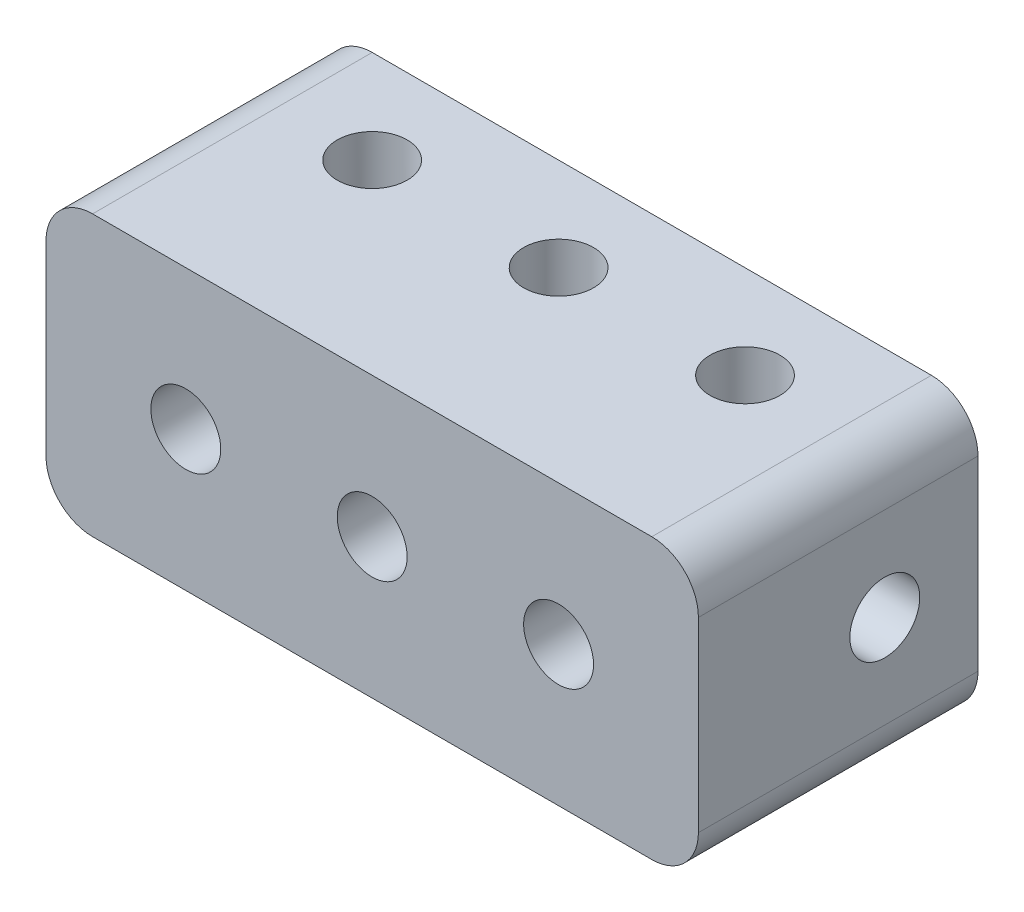
SolidWorks part; units mm, degrees
ref_plane "Front Plane" through (0, 0, 0) normal (0, 0, 1) x (1, 0, 0)
ref_plane "Top Plane" through (0, 0, 0) normal (0, 1, 0) x (1, 0, 0)
ref_plane "Right Plane" through (0, 0, 0) normal (1, 0, 0) x (0, 0, -1)
sketch "Sketch2" plane through (0, 0, 0) normal (0, 0, 1) x (1, 0, 0)
  line L1 (3.175, 0) -> (41.275, 0)
  line L2 (0, 3.175) -> (0, 15.875)
  line L3 (3.175, 19.05) -> (41.275, 19.05)
  line L4 (44.45, 3.175) -> (44.45, 15.875)
  arc A0 (0, 15.875) -> (3.175, 19.05) centre (3.175, 15.875) cw
  arc A1 (41.275, 19.05) -> (44.45, 15.875) centre (41.275, 15.875) cw
  arc A2 (3.175, 0) -> (0, 3.175) centre (3.175, 3.175) cw
  arc A3 (41.275, 0) -> (44.45, 3.175) centre (41.275, 3.175) ccw
  point P7 (0, 19.05)
  point P10 (44.45, 19.05)
  point P13 (0, 0)
  point P16 (44.45, 0)
  dimension "D3" = 3.175
  dimension "D4" = 3.175
  dimension "D5" = 3.175
  dimension "D6" = 3.175
  dimension "D1" = 44.45
  dimension "D2" = 19.05
extrude "Boss-Extrude1" add sketch "Sketch2" along normal blind 19.05
sketch "Sketch3" plane through (0, 0, 0) normal (0, 0, -1) x (-1, 0, 0)
  line L0 (-34.925, 9.525) -> (-9.525, 9.525) construction
  line L1 (-34.925, 14.2875) -> (-9.525, 14.2875)
  line L2 (-34.925, 4.7625) -> (-9.525, 4.7625)
  line L3 (-41.275, 19.05) -> (-3.175, 19.05) construction
  line L4 (-3.175, 0) -> (-41.275, 0) construction
  line L6 (0, 15.875) -> (0, 3.175) construction
  line L7 (-44.45, 3.175) -> (-44.45, 15.875) construction
  arc A0 (-34.925, 14.2875) -> (-34.925, 4.7625) centre (-34.925, 9.525) ccw
  arc A1 (-9.525, 4.7625) -> (-9.525, 14.2875) centre (-9.525, 9.525) ccw
  point P2 (-22.225, 9.525)
  point P15 (0, 0)
  dimension "D3" = 9.525
  dimension "D4" = 9.525
  dimension "D1" = 4.7625
  dimension "D2" = 4.7625
extrude "Cut-Extrude1" cut sketch "Sketch3" against normal blind 14.1224
sketch "Sketch4" plane through (0, 19.05, 0) normal (0, 1, 0) x (1, 0, 0)
  line L0 (44.45, -19.05) -> (44.45, 0) construction
  line L1 (41.275, -19.05) -> (3.175, -19.05) construction
  line L2 (0, -19.05) -> (0, 0) construction
  circle A0 centre (34.925, -6.35) radius 2.3812
  circle A1 centre (22.225, -6.35) radius 2.3813
  circle A2 centre (9.525, -6.35) radius 2.3812
  point P8 (23.4271, -6.8938)
  point P11 (7.6432, -7.3373)
  dimension "D1" = 9.525
  dimension "D2" = 12.7
  dimension "D3" = 4.7625
  dimension "D4" = 4.7625
  dimension "D5" = 4.7625
  dimension "D6" = 9.525
  dimension "D7" = 12.7
  dimension "D8" = 12.7
  dimension "D9" = 12.7
extrude "Cut-Extrude2" cut sketch "Sketch4" against normal through all both and the other way through all
sketch "Sketch5" plane through (44.45, 0, 0) normal (1, 0, 0) x (0, 0, -1)
  line L0 (0, 3.175) -> (0, 15.875) construction
  line L1 (-19.05, 0) -> (0, 0) construction
  circle A0 centre (-6.35, 9.525) radius 2.3813
  dimension "D1" = 6.35
  dimension "D2" = 4.7625
  dimension "D3" = 9.525
extrude "Cut-Extrude3" cut sketch "Sketch5" against normal through all both and the other way through all
sketch "Sketch7" plane through (0, 0, 19.05) normal (0, 0, 1) x (1, 0, 0)
  line L0 (44.45, 3.175) -> (44.45, 15.875) construction
  line L1 (0, 15.875) -> (0, 3.175) construction
  line L2 (3.175, 0) -> (41.275, 0) construction
  circle A0 centre (22.225, 9.525) radius 2.3813
  circle A1 centre (34.925, 9.525) radius 2.3812
  circle A2 centre (9.525, 9.525) radius 2.3813
  dimension "D1" = 4.7625
  dimension "D2" = 4.7625
  dimension "D3" = 4.7625
  dimension "D4" = 12.7
  dimension "D6" = 9.525
  dimension "D7" = 9.525
  dimension "D8" = 9.525
  dimension "D9" = 9.525
  dimension "D5" = 12.7
extrude "Cut-Extrude4" cut sketch "Sketch7" against normal through all both and the other way through all
